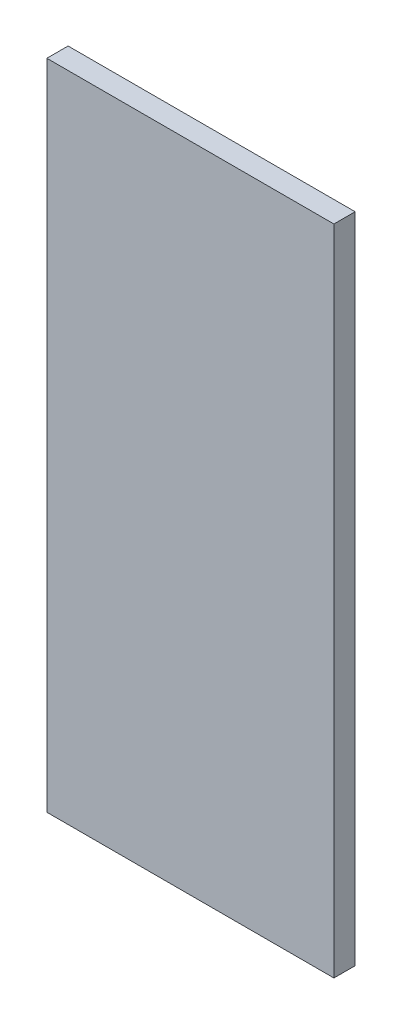
SolidWorks part; units mm, degrees
ref_plane "Front Plane" through (0, 0, 0) normal (0, 0, 1) x (1, 0, 0)
ref_plane "Top Plane" through (0, 0, 0) normal (0, 1, 0) x (1, 0, 0)
ref_plane "Right Plane" through (0, 0, 0) normal (1, 0, 0) x (0, 0, -1)
sketch "Sketch1" plane through (0, 0, 0) normal (0, 0, 1) x (1, 0, 0)
  line L0 (-13.5173, -15.169) -> (13.5173, -15.169)
  line L1 (-13.5173, 46.3338) -> (13.5173, 46.3338)
  line L2 (-13.5173, 46.3338) -> (-13.5173, -18.169)
  line L3 (-13.5173, -18.169) -> (13.5173, -18.169)
  line L4 (13.5173, 46.3338) -> (13.5173, -18.169)
  line L5 (11.5173, -15.169) -> (-11.5173, -15.169) construction
extrude "Boss-Extrude1" add sketch "Sketch1" along normal blind 2 contours L4 L1 L2 L0
sketch "Sketch2" plane through (0, 0, 0) normal (0, 0, -1) x (-1, 0, 0)
  line L0 (-11.5173, 44.3338) -> (11.5173, 44.3338) construction
  line L1 (-11.5173, -15.169) -> (-11.5173, 44.3338) construction
  line L2 (-11.5173, -15.169) -> (11.5173, -15.169) construction
  line L3 (11.5173, -15.169) -> (11.5173, 44.3338) construction
  line L4 (-11.5173, 44.3338) -> (11.5173, 44.3338)
  line L5 (-11.5173, -15.169) -> (-11.5173, 44.3338)
  line L6 (-11.5173, -15.169) -> (11.5173, -15.169)
  line L7 (11.5173, -15.169) -> (11.5173, 44.3338) construction
  line L8 (11.2173, -14.869) -> (11.2173, 44.0338)
  line L9 (-11.2173, 44.0338) -> (11.2173, 44.0338)
  line L10 (-11.2173, -14.869) -> (-11.2173, 44.0338)
  line L11 (-11.2173, -14.869) -> (11.2173, -14.869)
  dimension "D1" = 0.3
extrude "Boss-Extrude2" add sketch "Sketch2" along normal blind 1 separate body contours L10 L11 L8 L9
sketch "Sketch3" plane through (0, -14.869, 0) normal (0, -1, 0) x (1, 0, 0)
  line L0 (11.2173, -0.8) -> (-11.2173, -0.8)
  line L1 (-11.2173, -0.8) -> (-11.2173, -1.2)
  line L2 (-11.2173, -1.2) -> (11.2173, -1.2)
  line L3 (11.2173, -1.2) -> (11.2173, -0.8)
  line L4 (11.5173, -1.5) -> (11.5173, -0.5)
  line L5 (-11.5173, -1.5) -> (11.5173, -1.5)
  line L6 (-11.5173, -0.5) -> (-11.5173, -1.5)
  line L7 (11.5173, -0.5) -> (-11.5173, -0.5)
  line L8 (11.5173, -1.5) -> (11.5173, -0.5)
  line L9 (-11.5173, -1.5) -> (11.5173, -1.5) construction
  line L10 (-11.5173, -0.5) -> (-11.5173, -1.5)
  line L11 (11.5173, -0.5) -> (-11.5173, -0.5)
  line M10 (-11.2173, 0) -> (-11.2173, -1)
  line M11 (-11.2173, -1) -> (11.2173, -1)
  line M12 (11.2173, -1) -> (11.2173, 0)
  dimension "D1" = 0
  dimension "D2" = 0.3
extrude "Boss-Extrude3" add sketch "Sketch3" along normal blind 0.6 separate body contours L2 L3 L1 M11 | L0 M12 M10 M11
